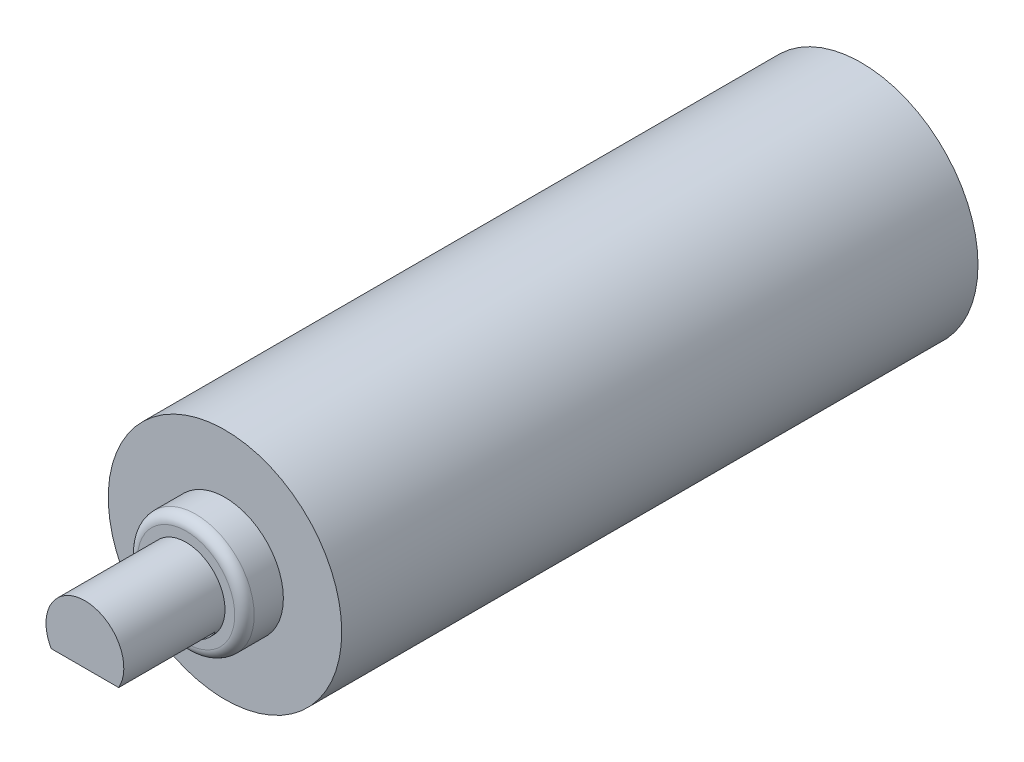
SolidWorks part; units mm, degrees
material "0.7033 (EN-GJS-350-22-LT)"
ref_plane "前视基准面" through (0, 0, 0) normal (0, 0, 1) x (1, 0, 0)
ref_plane "上视基准面" through (0, 0, 0) normal (0, 1, 0) x (1, 0, 0)
ref_plane "右视基准面" through (0, 0, 0) normal (1, 0, 0) x (0, 0, -1)
sketch "草图1" plane through (0, 0, 0) normal (0, 0, 1) x (1, 0, 0)
  circle A0 centre (0, 0) radius 3
  dimension "D1" = 6
extrude "凸台-拉伸1" add sketch "草图1" against normal blind 16.35
sketch "草图2" plane through (0, 0, 0) normal (0, 0, 1) x (1, 0, 0)
  circle A0 centre (0, 0) radius 1.5
  dimension "D1" = 3
extrude "凸台-拉伸2" add sketch "草图2" along normal blind 1
sketch "草图3" plane through (0, 0, 1) normal (0, 0, 1) x (1, 0, 0)
  circle A0 centre (0, 0) radius 1
  dimension "D1" = 2
extrude "凸台-拉伸3" add sketch "草图3" along normal blind 2.6
sketch "草图4" plane through (0, 0, 3.6) normal (0, 0, 1) x (1, 0, 0)
  line L0 (0, 1) -> (0, -0.5) construction
  line L2 (0, -0.5) -> (0.8625, -0.5)
  line L4 (0, -1) -> (0.8625, -1)
  line L5 (0.8625, -0.5) -> (0.8625, -1)
  line L6 (0, -0.5) -> (-0.8694, -0.5)
  line L8 (0, -1) -> (-0.8694, -1)
  line L9 (-0.8694, -0.5) -> (-0.8694, -1)
  circle A0 centre (0, 0) radius 1 construction
  circle A1 centre (0, 0) radius 1 construction
  dimension "D1" = 1.5
extrude "切除-拉伸1" cut sketch "草图4" against normal blind 2.5
fillet "圆角1" radius 0.25 1 edges at (1.5, 0, 1)
